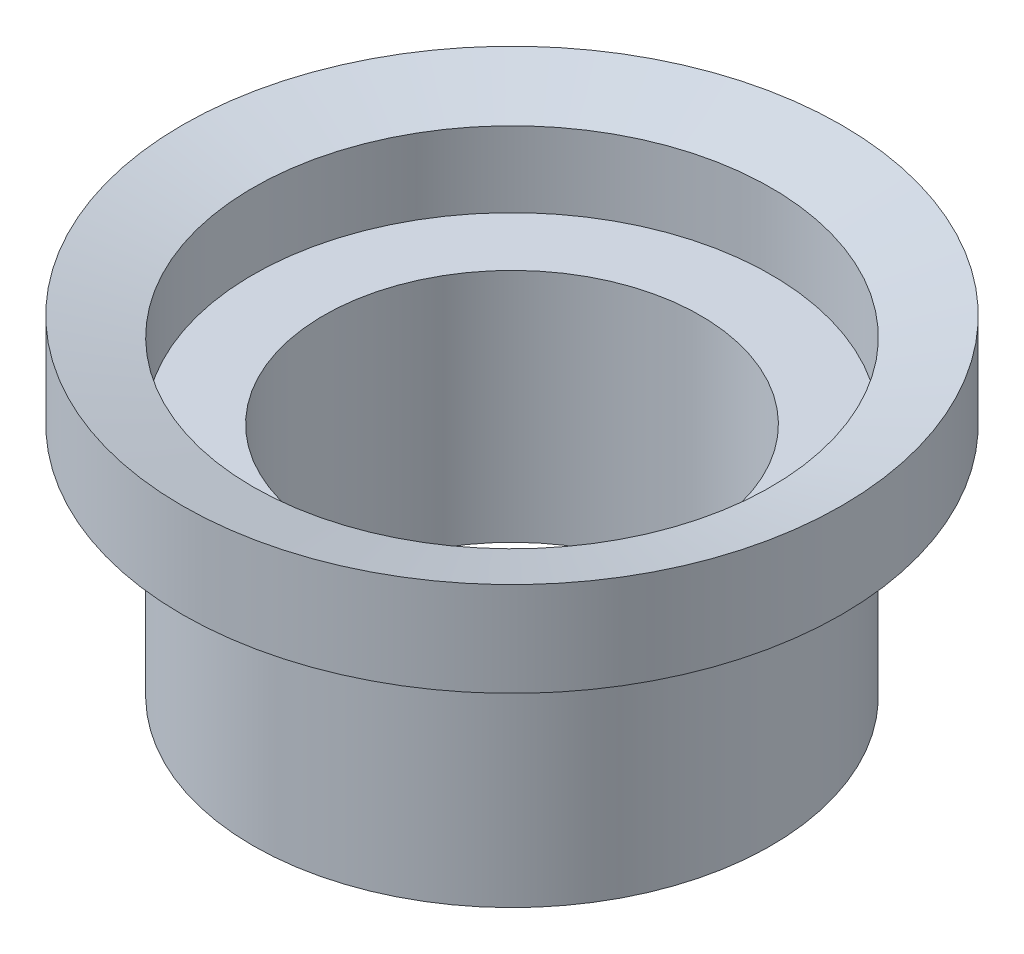
SolidWorks part; units mm, degrees
ref_plane "Front Plane" through (0, 0, 0) normal (0, 0, 1) x (1, 0, 0)
ref_plane "Top Plane" through (0, 0, 0) normal (0, 1, 0) x (1, 0, 0)
ref_plane "Right Plane" through (0, 0, 0) normal (1, 0, 0) x (0, 0, -1)
sketch "Sketch1" plane through (0, 0, 0) normal (0, 1, 0) x (1, 0, 0)
  circle A0 centre (0, 0) radius 16.5
  circle A1 centre (0, 0) radius 12
  dimension "D1" = 33
  dimension "D2" = 24
extrude "Boss-Extrude1" add sketch "Sketch1" along normal blind 15
sketch "Sketch2" plane through (0, 15, 0) normal (0, 1, 0) x (1, 0, 0)
  circle A0 centre (0, 0) radius 21
  circle A1 centre (0, 0) radius 16.5
  dimension "D1" = 42
extrude "Boss-Extrude2" add sketch "Sketch2" along normal blind 6 separate body
sketch "Sketch3" plane through (0, 0, 0) normal (0, 0, 1) x (1, 0, 0)
  line L0 (0, 0) -> (0, 33.2857) construction
  line L2 (0, 21) -> (-21, 21)
  line L5 (-21, 21) -> (0, 15.3731)
  line L6 (0, 15.3731) -> (0, 21)
revolve "Cut-Revolve1" cut sketch "Sketch3" angle 360 about L0
